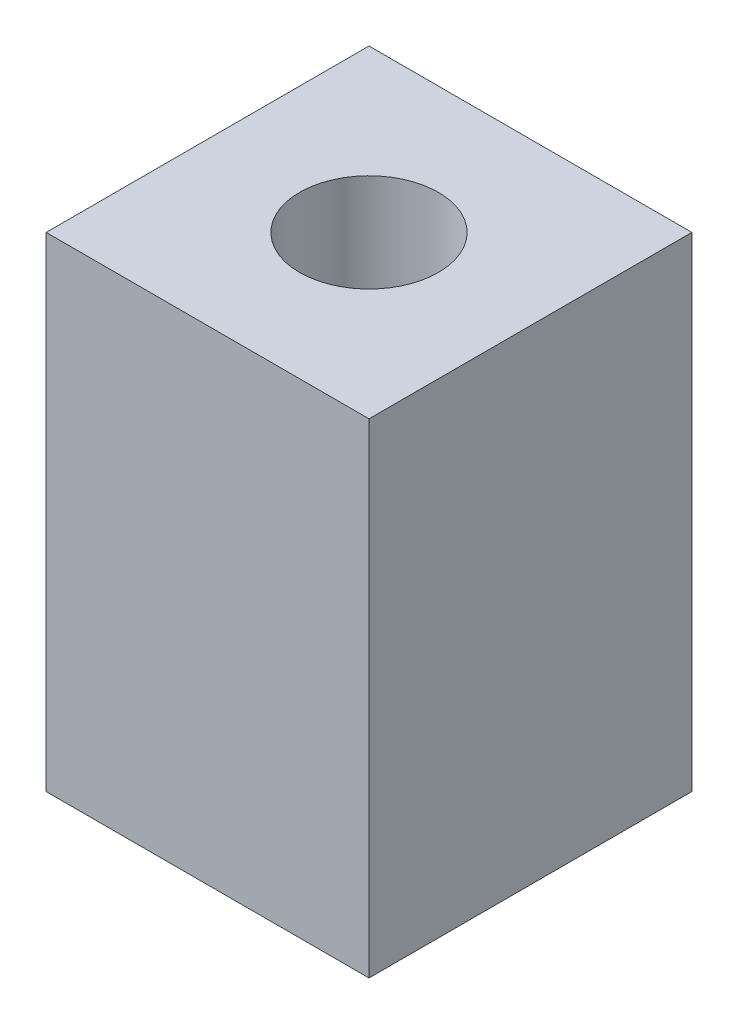
SolidWorks part; units mm, degrees
ref_plane "Front Plane" through (0, 0, 0) normal (0, 0, 1) x (1, 0, 0)
ref_plane "Top Plane" through (0, 0, 0) normal (0, 1, 0) x (1, 0, 0)
ref_plane "Right Plane" through (0, 0, 0) normal (1, 0, 0) x (0, 0, -1)
sketch "Sketch1" plane through (0, 0, 0) normal (0, 1, 0) x (1, 0, 0)
  line L1 (-20, 10) -> (0, 10)
  line L2 (-20, 10) -> (-20, -10)
  line L3 (-20, -10) -> (0, -10)
  line L4 (0, 10) -> (0, -10)
  dimension "D1" = 20
extrude "Boss-Extrude1" add sketch "Sketch1" along normal blind 30
sketch "Sketch2" plane through (0, 30, 0) normal (0, 1, 0) x (1, 0, 0)
  line L4 (-20, -10) -> (0, -10) construction
  circle A0 centre (-10, 0) radius 4.3
  point P2 (0, 0)
  point P3 (-9.6273, -2.5143)
  point P4 (0, 0)
  point P5 (0, 0)
  point P8 (-10, -10)
  dimension "D1" = 8.6
extrude "Cut-Extrude1" cut sketch "Sketch2" against normal through all
